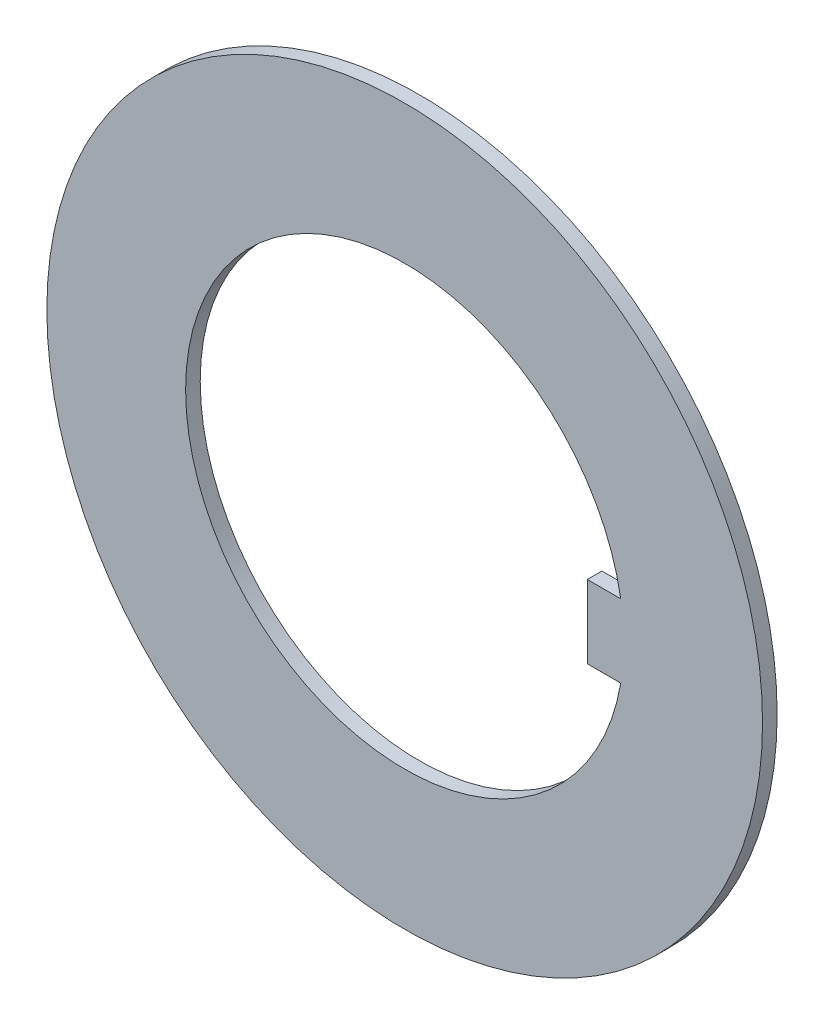
SolidWorks part; units mm, degrees
material "1.0037 (S235JR)"
ref_plane "Front Plane" through (0, 0, 0) normal (0, 0, 1) x (1, 0, 0)
ref_plane "Top Plane" through (0, 0, 0) normal (0, 1, 0) x (1, 0, 0)
ref_plane "Right Plane" through (0, 0, 0) normal (1, 0, 0) x (0, 0, -1)
sketch "Sketch1" plane through (0, 0, 0) normal (0, 1, 0) x (1, 0, 0)
  line L0 (15, 88) -> (24.5, 88)
  line L1 (24.5, 88) -> (24.5, 89)
  line L2 (24.5, 89) -> (15, 89)
  line L3 (15, 89) -> (15, 88)
  line L4 (0, -150) -> (0, 150) construction
revolve "REV_MB6_30x49x1" add sketch "Sketch1" angle 360 about L4
sketch "Sketch2" plane through (0, 0, 0) normal (0, 1, 0) x (1, 0, 0)
  line L1 (12.5, 88) -> (15.2, 88)
  line L2 (12.5, 88) -> (12.5, 89)
  line L3 (12.5, 89) -> (15.2, 89)
  line L4 (15.2, 88) -> (15.2, 89)
extrude "EX_Inner_Tab_5mm_M27.5" add sketch "Sketch2" along normal mid plane 5
